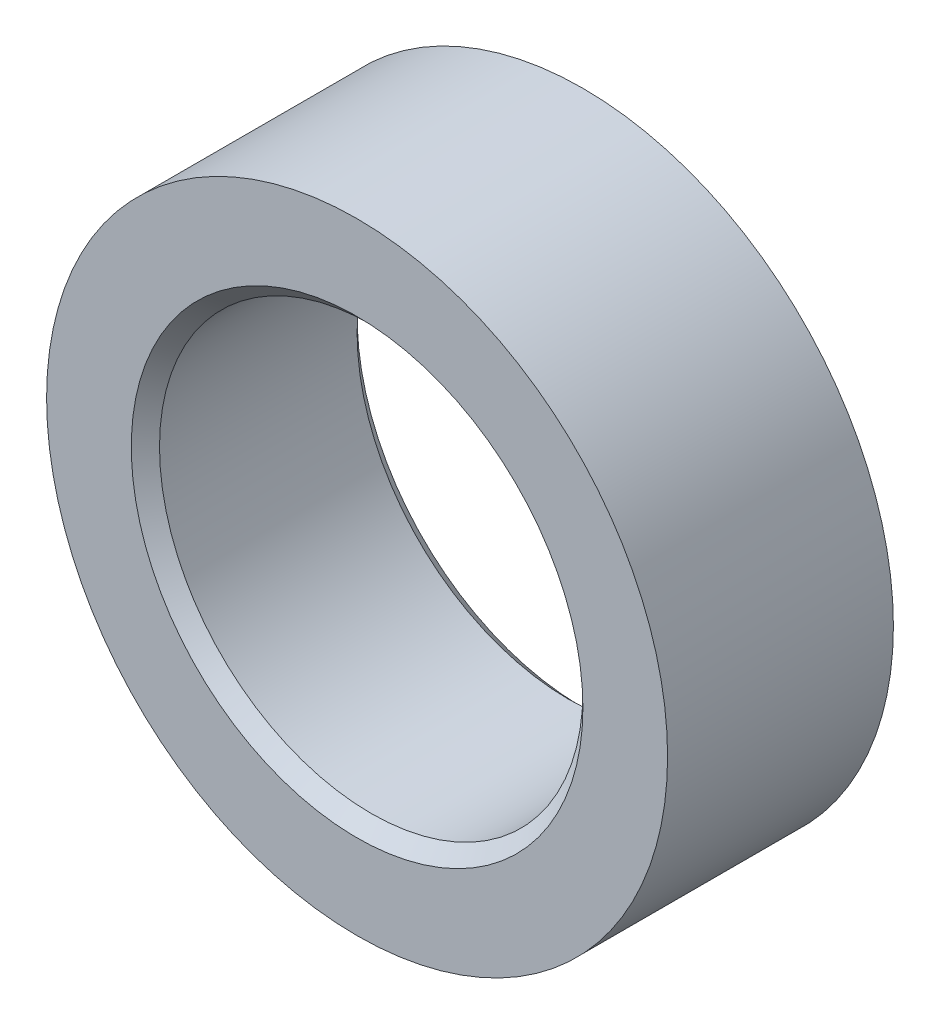
SolidWorks part; units mm, degrees
ref_plane "Front Plane" through (0, 0, 0) normal (1, 0, 0) x (0, 1, 0)
ref_plane "Top Plane" through (0, 0, 0) normal (0, 0, 1) x (0, 1, 0)
ref_plane "Right Plane" through (0, 0, 0) normal (0, 1, 0) x (-1, 0, 0)
sketch "Sketch1" plane through (0, 0, 0) normal (0, 0, 1) x (0, 1, 0)
  circle A0 centre (0, 0) radius 11
  circle A1 centre (0, 0) radius 7.5
  dimension "D1" = 22
  dimension "D2" = 15
extrude "Boss-Extrude1" add sketch "Sketch1" along normal mid plane 8
chamfer "Chamfer1" distance 0.5 angle 45 2 edges at (7.5, 0, 4) (7.5, 0, -4)
